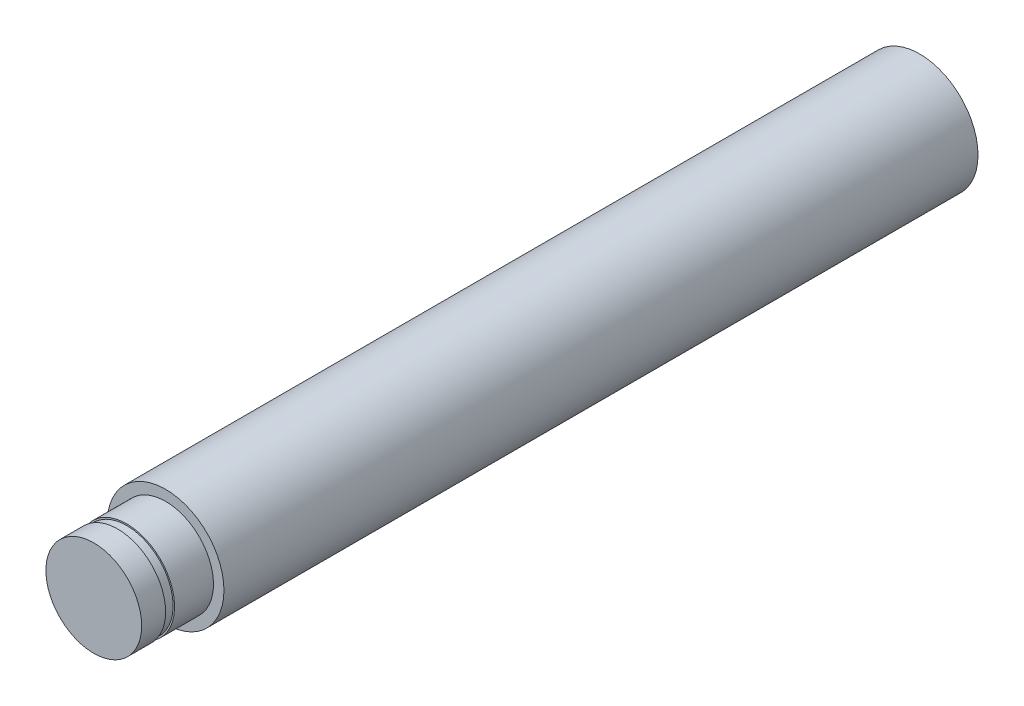
SolidWorks part; units mm, degrees
material "Cast Alloy Steel"
ref_plane "Front Plane" through (0, 0, 0) normal (0, 0, 1) x (1, 0, 0)
ref_plane "Top Plane" through (0, 0, 0) normal (0, 1, 0) x (1, 0, 0)
ref_plane "Right Plane" through (0, 0, 0) normal (1, 0, 0) x (0, 0, -1)
sketch "Sketch1" plane through (0, 0, 0) normal (0, 0, 1) x (1, 0, 0)
  circle A0 centre (0, 0) radius 2.4765
  dimension "D1" = 4.953
extrude "Boss-Extrude1" add sketch "Sketch1" along normal blind 32.004
sketch "Sketch2" plane through (0, 0, 32.004) normal (0, 0, 1) x (1, 0, 0)
  circle A0 centre (0, 0) radius 2.032
  dimension "D1" = 4.064
extrude "Boss-Extrude2" add sketch "Sketch2" along normal blind 1.651
sketch "Sketch3" plane through (0, 0, 33.655) normal (0, 0, 1) x (1, 0, 0)
  circle A0 centre (0, 0) radius 1.9685
  dimension "D1" = 3.937
extrude "Boss-Extrude3" add sketch "Sketch3" along normal blind 0.381
sketch "Sketch4" plane through (0, 0, 34.036) normal (0, 0, 1) x (1, 0, 0)
  circle A0 centre (0, 0) radius 2.032
  dimension "D1" = 4.064
extrude "Boss-Extrude4" add sketch "Sketch4" along normal blind 1.016
